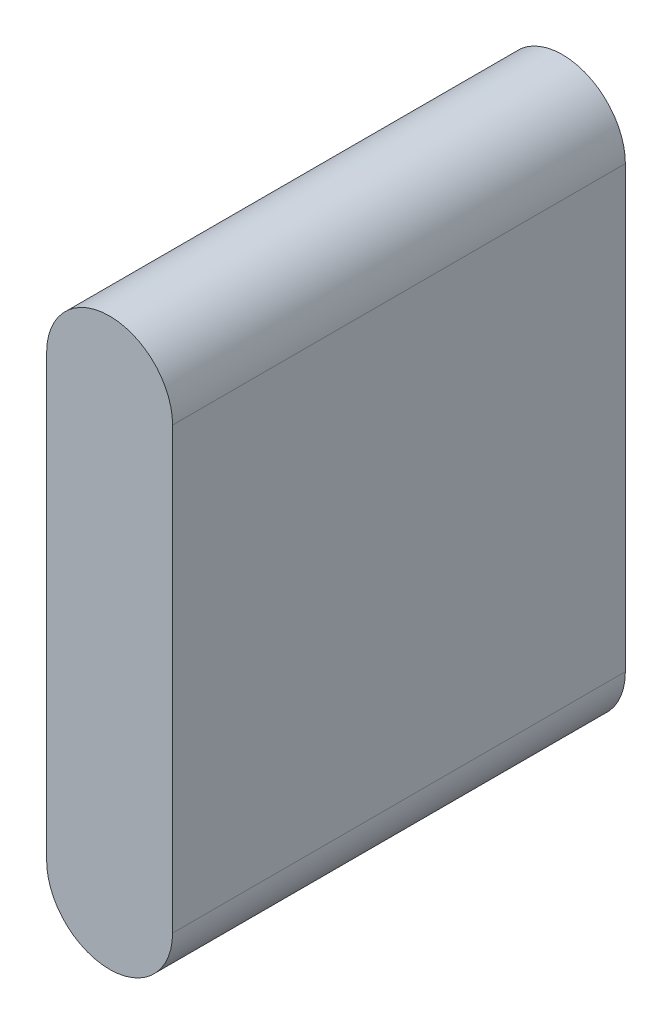
SolidWorks part; units mm, degrees
ref_plane "Front Plane" through (0, 0, 0) normal (0, 0, 1) x (1, 0, 0)
ref_plane "Top Plane" through (0, 0, 0) normal (0, 1, 0) x (1, 0, 0)
ref_plane "Right Plane" through (0, 0, 0) normal (1, 0, 0) x (0, 0, -1)
sketch "Sketch1" plane through (0, 0, 0) normal (1, 0, 0) x (0, 0, -1)
  line L1 (-51.9208, 41.7052) -> (28.0792, 41.7052)
  line L2 (-51.9208, 41.7052) -> (-51.9208, -58.2948)
  line L3 (-51.9208, -58.2948) -> (28.0792, -58.2948)
  line L4 (28.0792, 41.7052) -> (28.0792, -58.2948)
  dimension "D1" = 80
  dimension "D2" = 100
extrude "Boss-Extrude1" add sketch "Sketch1" against normal blind 22.25
sketch "Sketch2" plane through (0, 0, -28.0792) normal (0, 0, -1) x (-1, 0, 0)
  line L0 (22.25, -58.2948) -> (22.25, -47.1648) construction
  line L1 (22.25, -47.1648) -> (0, -47.1648) construction
  line L2 (0, -58.2948) -> (0, 41.7052) construction
  line L3 (22.25, -8.2948) -> (0, -8.2948) construction
  line L4 (22.25, -58.2948) -> (22.25, 41.7052) construction
  line L5 (22.25, -47.1648) -> (22.25, -58.2948)
  line L6 (22.25, -58.2948) -> (0, -58.2948)
  line L7 (0, -58.2948) -> (0, -47.1648)
  line L8 (0, 41.7052) -> (0, 30.5752)
  line L9 (22.25, 41.7052) -> (0, 41.7052)
  line L10 (22.25, 30.5752) -> (22.25, 41.7052)
  arc A0 (22.25, -47.1648) -> (0, -47.1648) centre (11.125, -47.1648) cw
  arc A1 (22.25, 30.5752) -> (0, 30.5752) centre (11.125, 30.5752) ccw
extrude "Cut-Extrude1" cut sketch "Sketch2" against normal through all
